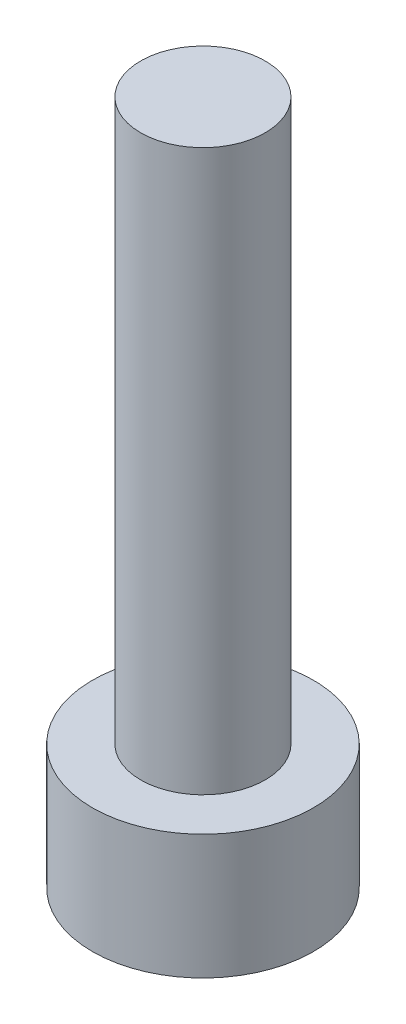
SolidWorks part; units mm, degrees
ref_plane "前视基准面" through (0, 0, 0) normal (0, 0, 1) x (1, 0, 0)
ref_plane "上视基准面" through (0, 0, 0) normal (0, 1, 0) x (1, 0, 0)
ref_plane "右视基准面" through (0, 0, 0) normal (1, 0, 0) x (0, 0, -1)
sketch "草图1" plane through (0, 0, 0) normal (0, 1, 0) x (1, 0, 0)
  circle A0 centre (0, 0) radius 3.55
  dimension "D1" = 7.1
extrude "凸台-拉伸1" add sketch "草图1" along normal blind 4
sketch "草图2" plane through (0, 4, 0) normal (0, 1, 0) x (1, 0, 0)
  circle A0 centre (0, 0) radius 2
  dimension "D1" = 4
extrude "凸台-拉伸2" add sketch "草图2" along normal blind 18
